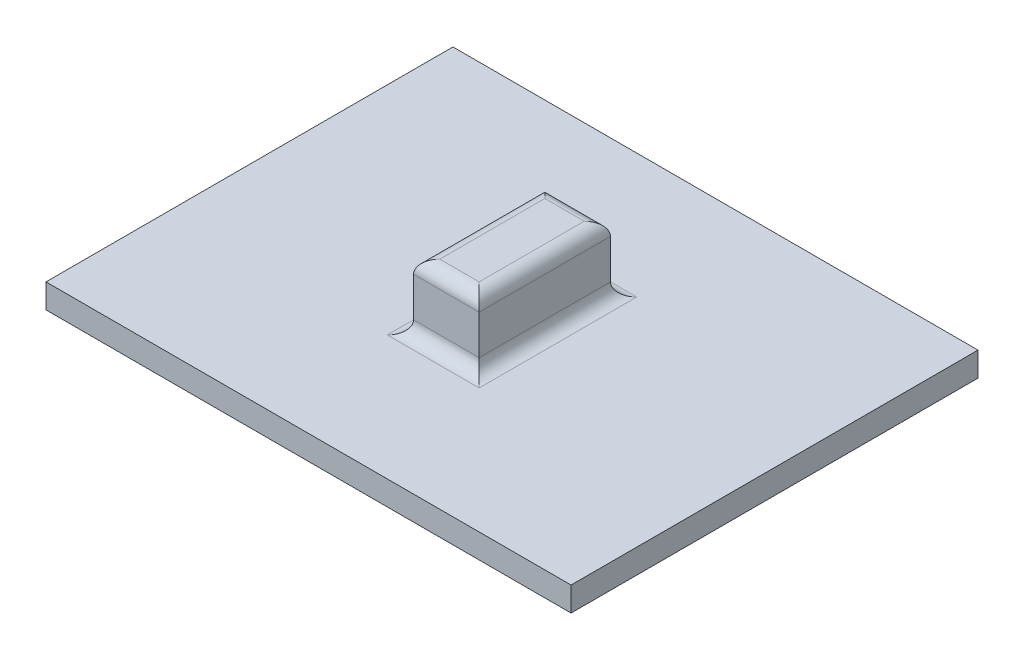
SolidWorks part; units mm, degrees
ref_plane "Front Plane" through (0, 0, 0) normal (0, 0, 1) x (1, 0, 0)
ref_plane "Top Plane" through (0, 0, 0) normal (0, 1, 0) x (1, 0, 0)
ref_plane "Right Plane" through (0, 0, 0) normal (1, 0, 0) x (0, 0, -1)
sketch "Sketch1" plane through (0, 0, 0) normal (0, 1, 0) x (1, 0, 0)
  line L1 (0, 0) -> (80, 0)
  line L2 (0, 0) -> (0, 62)
  line L3 (0, 62) -> (80, 62)
  line L4 (80, 0) -> (80, 62)
  dimension "D1" = 80
  dimension "D2" = 62
extrude "Boss-Extrude1" add sketch "Sketch1" along normal blind 3.7
sketch "Sketch2" plane through (0, 3.7, 0) normal (0, 1, 0) x (1, 0, 0)
  line L0 (80, 0) -> (80, 62) construction
  line L1 (35, 41) -> (45, 41)
  line L2 (35, 41) -> (35, 21)
  line L3 (35, 21) -> (45, 21)
  line L4 (45, 41) -> (45, 21)
  line L5 (80, 62) -> (0, 62) construction
  point P6 (80, 31)
  point P7 (45, 31)
  point P8 (40, 41)
  point P11 (40, 62)
  dimension "D1" = 10
  dimension "D2" = 20
extrude "Boss-Extrude2" add sketch "Sketch2" along normal blind 10
fillet "Fillet1" radius 2 4 edges at (40, 3.7, -41) (45, 3.7, -31) (40, 3.7, -21) (35, 3.7, -31)
fillet "Fillet2" radius 2 4 edges at (40, 13.7, -41) (45, 13.7, -31) (40, 13.7, -21) (35, 13.7, -31)
